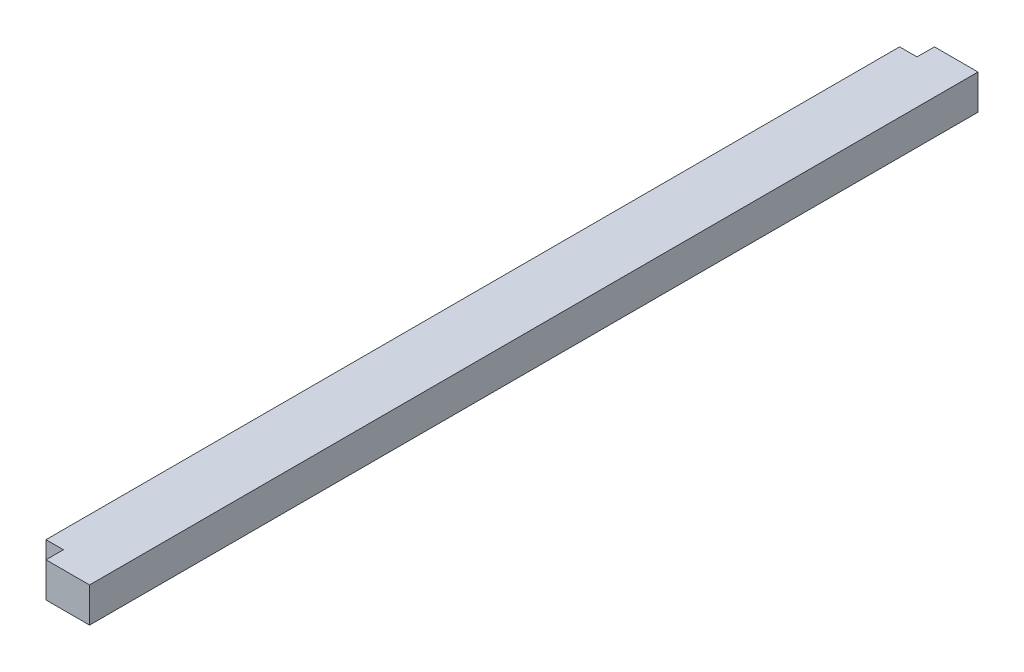
SolidWorks part; units mm, degrees
material "Сосна"
ref_plane "Спереди" through (0, 0, 0) normal (0, 0, 1) x (1, 0, 0)
ref_plane "Сверху" through (0, 0, 0) normal (0, 1, 0) x (1, 0, 0)
ref_plane "Справа" through (0, 0, 0) normal (1, 0, 0) x (0, 0, -1)
sketch "Эскиз1" plane through (0, 0, 0) normal (0, 0, -1) x (1, 0, 0)
  line L0 (0, 10) -> (10, 10)
  line L1 (0, 0) -> (35, 0)
  line L2 (0, 0) -> (0, 10)
  line L3 (10, 20) -> (35, 20)
  line L4 (35, 0) -> (35, 20)
  line L5 (10, 10) -> (10, 20)
  dimension "D1" = 35
  dimension "D2" = 20
  dimension "D3" = 10
  dimension "D4" = 10
extrude "Бобышка-Вытянуть1" add sketch "Эскиз1" along normal blind 510
sketch "Эскиз2" plane through (0, 0, 0) normal (0, 1, 0) x (1, 0, 0)
  line L0 (35, 255) -> (0, 255) construction
  line L1 (0, 0) -> (10, 0)
  line L2 (0, 0) -> (0, 10)
  line L3 (0, 10) -> (10, 10)
  line L4 (10, 0) -> (10, 10)
  line L5 (35, 510) -> (35, 0) construction
  line L6 (0, 510) -> (0, 0) construction
  line L7 (10, 510) -> (10, 500)
  line L8 (0, 500) -> (10, 500)
  line L9 (0, 510) -> (0, 500)
  line L10 (0, 510) -> (10, 510)
  dimension "D1" = 10
  dimension "D2" = 10
extrude "Вырез-Вытянуть1" cut sketch "Эскиз2" against normal through all
